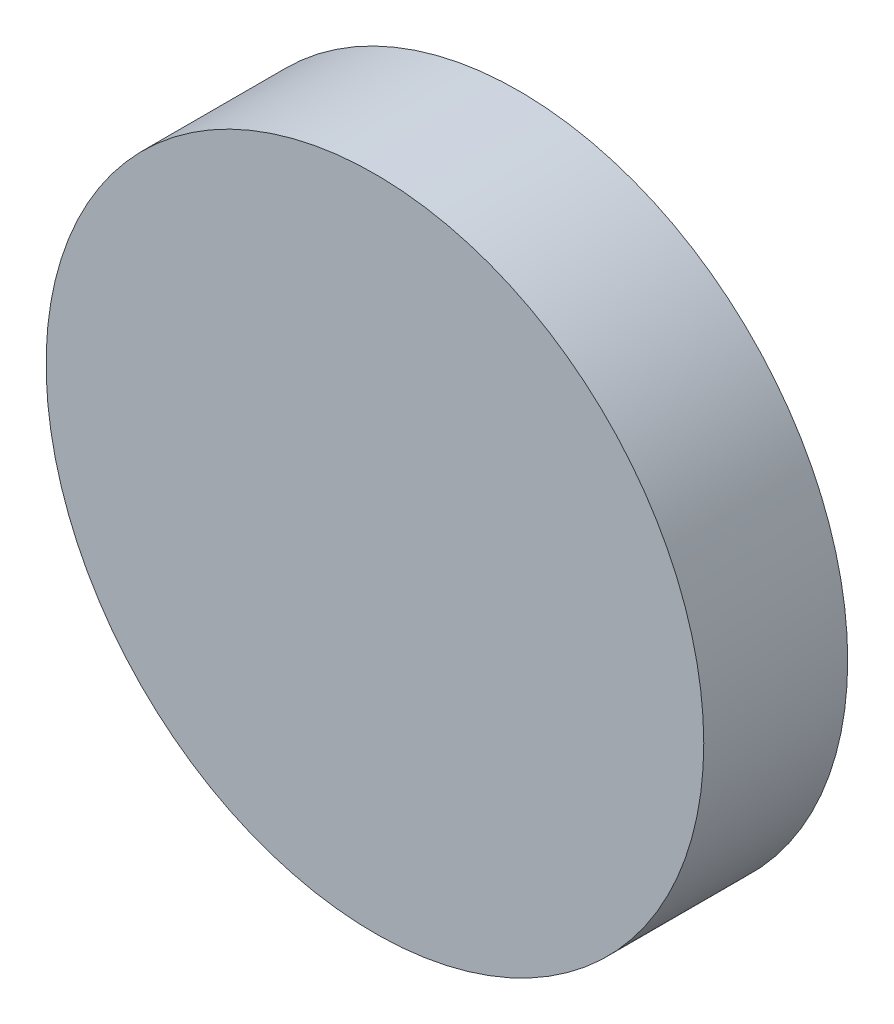
SolidWorks part; units mm, degrees
ref_plane "Plano frontal" through (0, 0, 0) normal (0, 0, 1) x (1, 0, 0)
ref_plane "Plano superior" through (0, 0, 0) normal (0, 1, 0) x (1, 0, 0)
ref_plane "Plano direito" through (0, 0, 0) normal (1, 0, 0) x (0, 0, -1)
sketch "Esboço1" plane through (0, 0, 0) normal (0, 0, 1) x (1, 0, 0)
  circle A0 centre (0, 0) radius 150
  dimension "D1" = 300
extrude "Ressalto-extrusão1" add sketch "Esboço1" along normal blind 100
ref_plane "Plano1" through (0, 0, 90) normal (0, 0, 1) x (1, 0, 0)
sketch "Esboço3" plane through (0, 0, 90) normal (0, 0, 1) x (1, 0, 0)
  circle A0 centre (0, 0) radius 5
  dimension "D1" = 10
extrude "Corte-extrusão1" cut sketch "Esboço3" against normal blind 100 draft 69 draft outward yes
